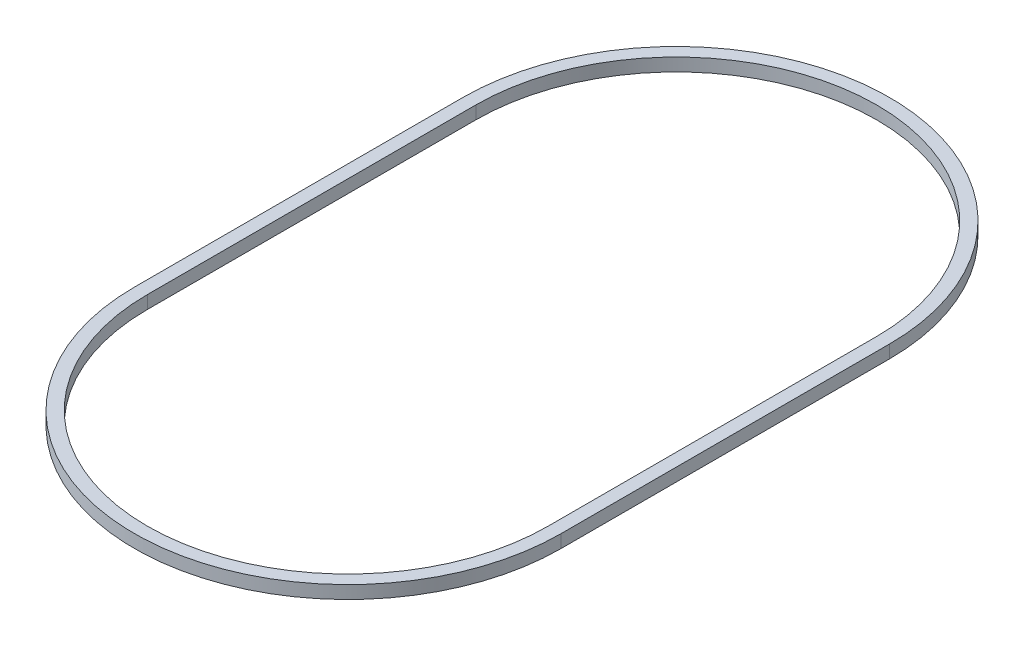
SolidWorks part; units mm, degrees
ref_plane "Plano frontal" through (0, 0, 0) normal (0, 0, 1) x (1, 0, 0)
ref_plane "Plano superior" through (0, 0, 0) normal (0, 1, 0) x (1, 0, 0)
ref_plane "Plano direito" through (0, 0, 0) normal (1, 0, 0) x (0, 0, -1)
sketch "Esboço1" plane through (0, 0, 0) normal (0, 1, 0) x (1, 0, 0)
  line L0 (0, 31.75) -> (0, -31.75) construction
  line L1 (38.75, 31.75) -> (38.75, -31.75)
  line L2 (-38.75, 31.75) -> (-38.75, -31.75)
  line L3 (0, 31.75) -> (0, -31.75) construction
  line L4 (41.25, 31.75) -> (41.25, -31.75)
  line L5 (-41.25, 31.75) -> (-41.25, -31.75)
  arc A0 (38.75, 31.75) -> (-38.75, 31.75) centre (0, 31.75) ccw
  arc A1 (-38.75, -31.75) -> (38.75, -31.75) centre (0, -31.75) ccw
  arc A2 (41.25, 31.75) -> (-41.25, 31.75) centre (0, 31.75) ccw
  arc A3 (-41.25, -31.75) -> (41.25, -31.75) centre (0, -31.75) ccw
  point P2 (0, 0)
  point P10 (0, 0)
  dimension "D1" = 63.5
  dimension "D2" = 77.5
  dimension "D3" = 82.5
extrude "Ressalto-extrusão1" add sketch "Esboço1" along normal blind 2.5
